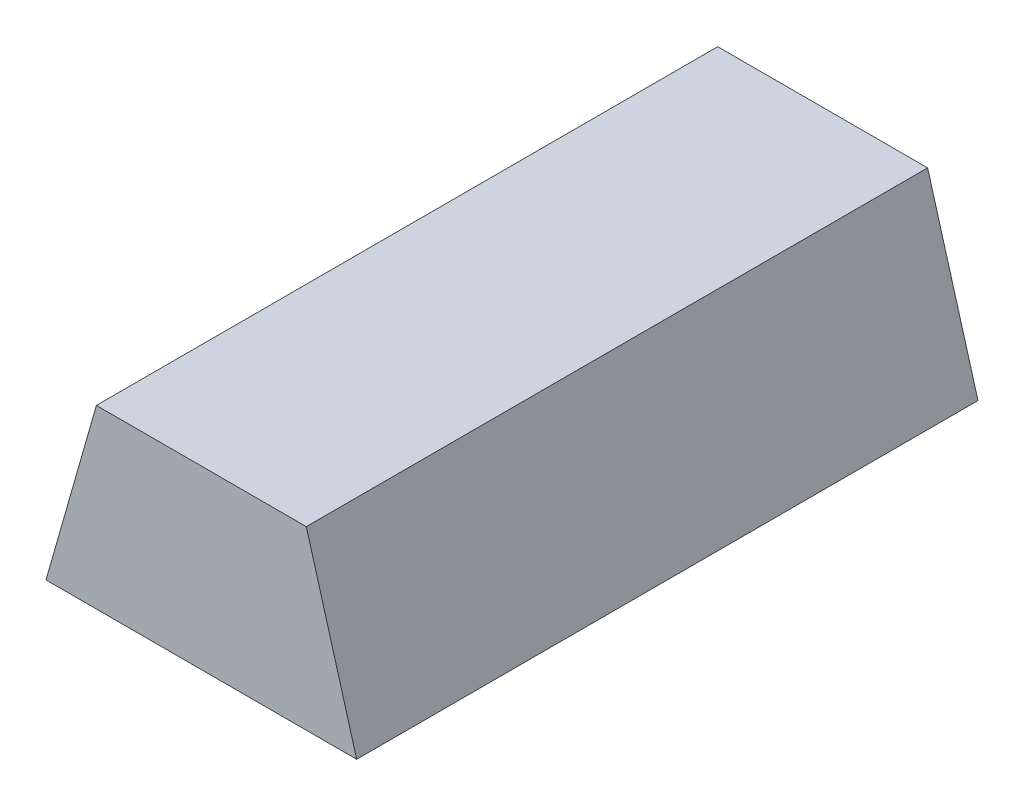
SolidWorks part; units mm, degrees
ref_plane "Front Plane" through (0, 0, 0) normal (0, 0, 1) x (1, 0, 0)
ref_plane "Top Plane" through (0, 0, 0) normal (0, 1, 0) x (1, 0, 0)
ref_plane "Right Plane" through (0, 0, 0) normal (1, 0, 0) x (0, 0, -1)
sketch "Sketch1" plane through (0, 0, 0) normal (0, 0, 1) x (1, 0, 0)
  line L0 (0, 64.4691) -> (0, -58.0443) construction
  line L1 (-71.1154, 0) -> (64.4691, 0) construction
  line L2 (-12.5, 10.5) -> (12.5, 10.5)
  line L3 (12.5, 10.5) -> (18.5, -10.5)
  line L4 (18.5, -10.5) -> (-18.5, -10.5)
  line L5 (-12.5, 10.5) -> (-18.5, -10.5)
  point P10 (0, -10.5)
  point P11 (0, 10.5)
  dimension "D1" = 12.5
  dimension "D2" = 18.5
  dimension "D3" = 10.5
  dimension "D4" = 10.5
extrude "Boss-Extrude1" add sketch "Sketch1" along normal blind 74
